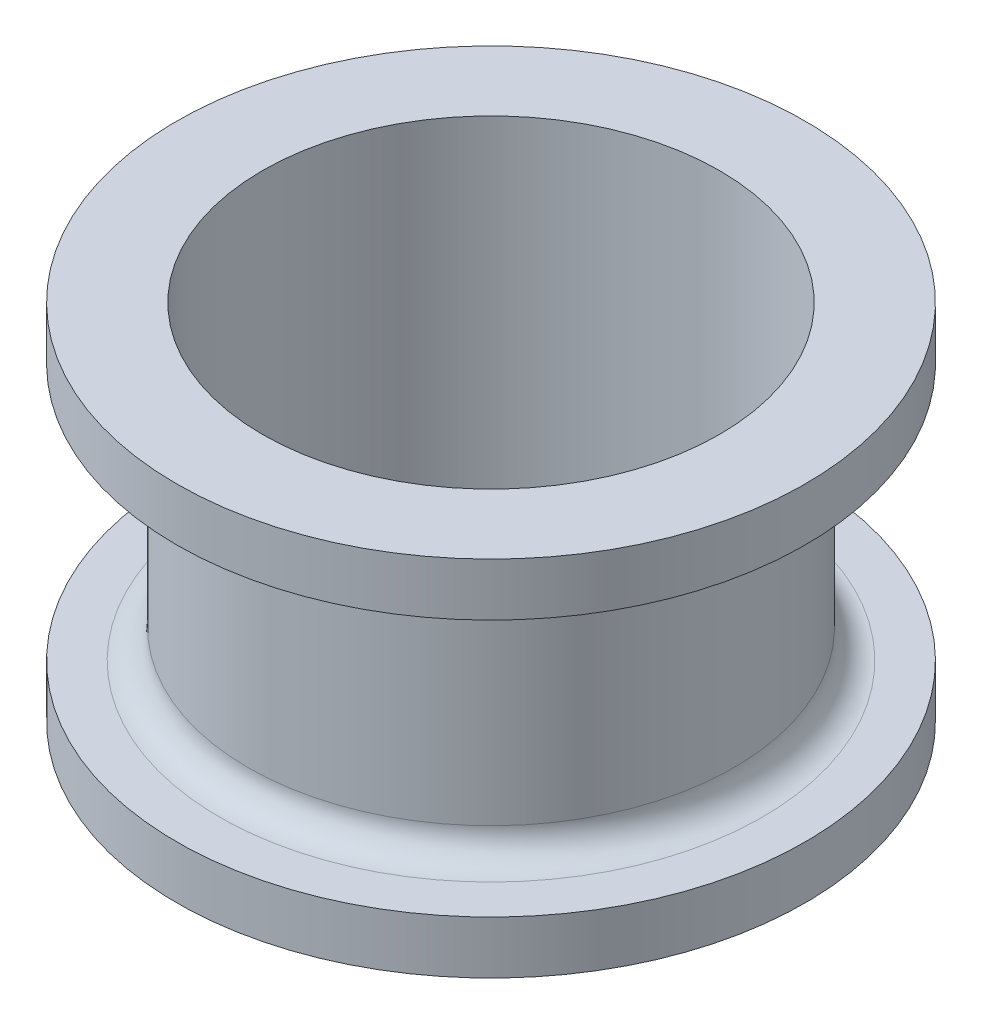
SolidWorks part; units mm, degrees
ref_plane "Front Plane" through (0, 0, 0) normal (0, 0, 1) x (1, 0, 0)
ref_plane "Top Plane" through (0, 0, 0) normal (0, 1, 0) x (1, 0, 0)
ref_plane "Right Plane" through (0, 0, 0) normal (1, 0, 0) x (0, 0, -1)
sketch "Sketch1" plane through (0, 0, 0) normal (0, 1, 0) x (1, 0, 0)
  circle A0 centre (0, 0) radius 8.5
  dimension "D1" = 17
extrude "Boss-Extrude1" add sketch "Sketch1" along normal blind 9
sketch "Sketch2" plane through (0, 9, 0) normal (0, 1, 0) x (1, 0, 0)
  circle A0 centre (0, 0) radius 11
  dimension "D1" = 22
extrude "Boss-Extrude2" add sketch "Sketch2" along normal blind 1.85
sketch "Sketch4" plane through (0, 0, 0) normal (0, -1, 0) x (1, 0, 0)
  circle A0 centre (0, 0) radius 11
extrude "Boss-Extrude4" add sketch "Sketch4" along normal blind 1.85
sketch "Sketch5" plane through (0, -1.85, 0) normal (0, -1, 0) x (1, 0, 0)
  circle A0 centre (0, 0) radius 8
  dimension "D1" = 16
extrude "Cut-Extrude1" cut sketch "Sketch5" against normal through all
fillet "Fillet1" radius 1 2 edges at (0, 0, 8.5) (0, 9, 8.5)
